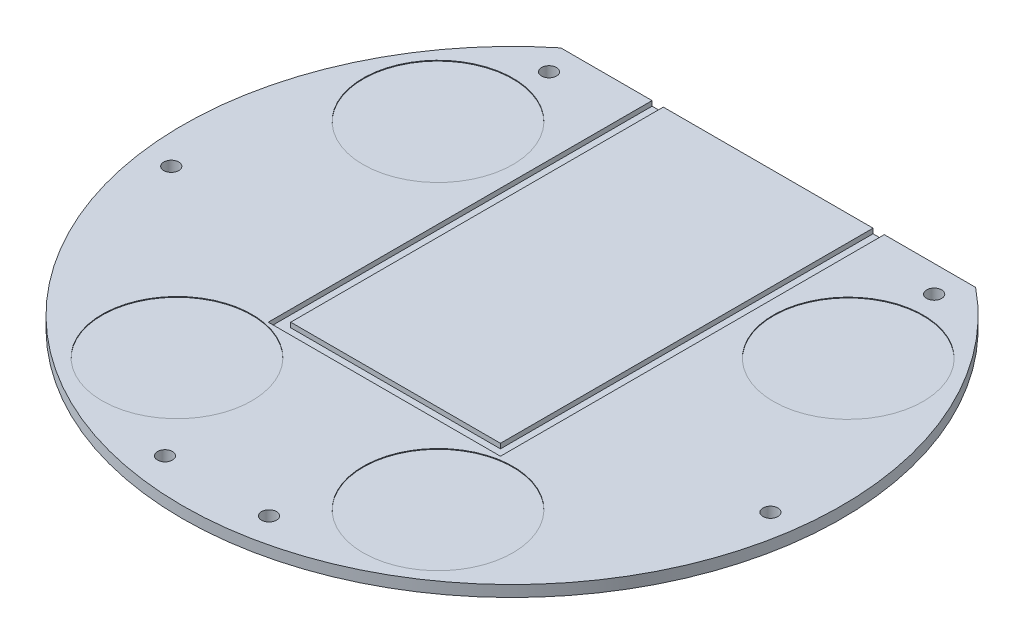
SolidWorks part; units mm, degrees
ref_plane "Front Plane" through (0, 0, 0) normal (0, 0, 1) x (1, 0, 0)
ref_plane "Top Plane" through (0, 0, 0) normal (0, 1, 0) x (1, 0, 0)
ref_plane "Right Plane" through (0, 0, 0) normal (1, 0, 0) x (0, 0, -1)
sketch "Sketch1" plane through (0, 0, 0) normal (0, 1, 0) x (1, 0, 0)
  line L0 (0, 0) -> (0, 68.3888)
  line L1 (0, 68.3888) -> (-55.3802, 68.3888)
  line L2 (-55.3802, 68.3888) -> (55.3802, 68.3888)
  line L3 (-55.3802, 68.3888) -> (0, 0) construction
  line L4 (55.3802, 68.3888) -> (0, 0) construction
  circle A0 centre (0, 0) radius 88
  dimension "D1" = 176
  dimension "D2" = 78
extrude "Boss-Extrude1" add sketch "Sketch1" along normal blind 3
sketch "Sketch3" plane through (0, 3, 0) normal (0, 1, 0) x (1, 0, 0)
  line L0 (0, 0) -> (0, -31.1)
  line L1 (0, -31.1) -> (-28, -31.1)
  line L2 (0, -31.1) -> (28, -31.1)
  line L3 (-28, -31.1) -> (-28, 68.3888)
  line L4 (55.3802, 68.3888) -> (-55.3802, 68.3888) construction
  line L5 (28, -31.1) -> (28, 68.3888)
  line L6 (-28, 68.3888) -> (-31, 68.3888)
  line L7 (28, 68.3888) -> (31, 68.3888)
  line L11 (-31, 68.3888) -> (-31, -34.1)
  line L12 (31, 68.3888) -> (31, -34.1)
  line L13 (31, -34.1) -> (-31, -34.1)
  line M11 (55.3802, 68.3888) -> (-55.3802, 68.3888)
extrude "Cut-Extrude2" cut sketch "Sketch3" against normal blind 1.3 contours L13 L12 L5 L2 L1 L3 L11 M11
sketch "Sketch4" plane through (0, 3, 0) normal (0, 1, 0) x (1, 0, 0)
  line L0 (0, 0) -> (54.772, 0)
  line L1 (54.772, 0) -> (54.772, 35)
  line L2 (0, 0) -> (-54.772, 0)
  line L3 (-54.772, 0) -> (-54.772, 35)
  line L4 (0, 0) -> (35, 0)
  line L5 (35, 0) -> (35, -54.772)
  line L6 (0, 0) -> (-35, 0)
  line L7 (-35, 0) -> (-35, -54.472)
  circle A0 centre (35, -54.772) radius 20
  circle A1 centre (-35, -54.472) radius 20
  circle A2 centre (54.772, 35) radius 20
  circle A3 centre (-54.772, 35) radius 20
extrude "Cut-Extrude3" cut sketch "Sketch4" against normal blind 0.2
sketch "Sketch5" plane through (0, 3, 0) normal (0, 1, 0) x (1, 0, 0)
  line L0 (0, 0) -> (-66.4894, 0)
  line L1 (0, 0) -> (-51.423, 61.2836)
  line L2 (0, 0) -> (71.3715, 0)
  line L3 (0, 0) -> (51.423, 61.2836)
  line L4 (0, 0) -> (-13.8919, -78.7846)
  line L5 (0, 0) -> (13.8919, -78.7846)
  dimension "D1" = 50
  dimension "D2" = 50
  dimension "D3" = 80
  dimension "D4" = 80
hole_wizard "Ø4.0mm Dowel Hole1" positions "3DSketch2" profile "Sketch7" hole size "Ø4.0" standard "ISO" end condition through all
sketch3d "3DSketch2"
  point P0 (-51.423, 3, -61.2836)
  point P3 (51.423, 3, -61.2836)
  point P6 (13.8919, 3, 78.7846)
  point P9 (-13.8919, 3, 78.7846)
sketch "Sketch7" plane through (-51.423, 3, -61.2836) normal (1, 0, 0) x (0, 0, 1)
  line L0 (0, 0) -> (0, 3)
  line L1 (0, 3) -> (2, 3)
  line L2 (2, 3) -> (2, 0)
  line L5 (2, 0) -> (0, 0)
  line L11 (0, -6.35) -> (0, 107.95) construction
  dimension "Thru Hole Dia." = 4
  dimension "Thru Hole Depth" = 3
sketch "Sketch8" plane through (0, 3, 0) normal (0, 1, 0) x (1, 0, 0)
  line L0 (0, 0) -> (-80, 0)
  line L1 (-80, 0) -> (-80, -11)
  line L2 (0, 0) -> (80, 0)
  line L3 (80, 0) -> (80, -11)
  circle A0 centre (-80, -11) radius 2
  circle A1 centre (80, -11) radius 2
  dimension "D1" = 4
  dimension "D2" = 4
  dimension "D3" = 80
  dimension "D4" = 80
  dimension "D5" = 11
  dimension "D6" = 11
extrude "Cut-Extrude4" cut sketch "Sketch8" against normal blind 19
